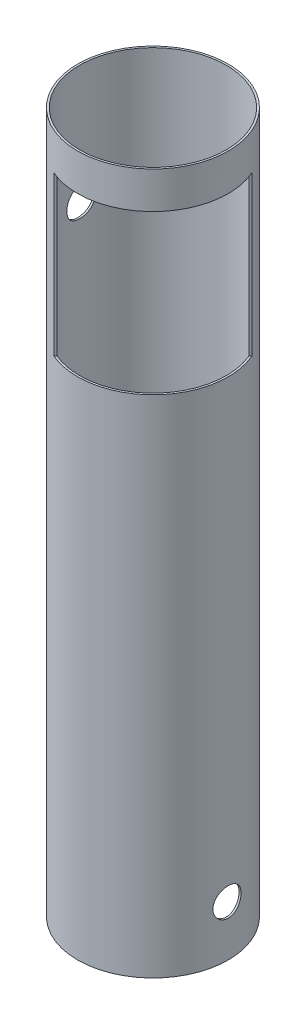
SolidWorks part; units mm, degrees
material "PVC Rígido"
ref_plane "Alzado" through (0, 0, 0) normal (0, 0, 1) x (1, 0, 0)
ref_plane "Planta" through (0, 0, 0) normal (0, 1, 0) x (1, 0, 0)
ref_plane "Vista lateral" through (0, 0, 0) normal (1, 0, 0) x (0, 0, -1)
sketch "Croquis1" plane through (0, 0, 0) normal (0, 1, 0) x (1, 0, 0)
  circle A0 centre (0, 0) radius 55.5
  circle A1 centre (0, 0) radius 57
  dimension "D1" = 111
  dimension "D2" = 114
extrude "Saliente-Extruir1" add sketch "Croquis1" along normal blind 530
ref_plane "Plano1" through (-57, 0, 0) normal (-1, 0, 0) x (0, 0, 1)
sketch "Croquis2" plane through (-57, 0, 0) normal (-1, 0, 0) x (0, 0, 1)
  line L0 (-57, 0) -> (57, 0) construction
  circle A0 centre (0, 440) radius 10.65
  dimension "D1" = 21.3
  dimension "D2" = 440
extrude "Cortar-Extruir1" cut sketch "Croquis2" against normal blind 10
ref_plane "Plano2" through (57, 0, 0) normal (1, 0, 0) x (0, 0, -1)
sketch "Croquis3" plane through (57, 0, 0) normal (1, 0, 0) x (0, 0, -1)
  line L0 (-57, 0) -> (57, 0) construction
  circle A0 centre (0, 38.1) radius 10.65
  dimension "D1" = 21.3
  dimension "D2" = 38.1
extrude "Cortar-Extruir3" cut sketch "Croquis3" against normal blind 10
ref_plane "Plano3" through (40.3051, 0, 40.3051) normal (0.7071, 0, 0.7071) x (0, -1, 0)
sketch "Croquis4" plane through (40.3051, 0, 40.3051) normal (0.7071, 0, 0.7071) x (0, -1, 0)
  line L1 (-502.0992, 60) -> (-382.0992, 60)
  line L2 (-502.0992, 60) -> (-502.0992, -60)
  line L3 (-502.0992, -60) -> (-382.0992, -60)
  line L4 (-382.0992, 60) -> (-382.0992, -60)
  line L6 (0, 57) -> (-530, 57) construction
  dimension "D1" = 120
  dimension "D2" = 120
  dimension "D3" = 3
extrude "Cortar-Extruir4" cut sketch "Croquis4" against normal blind 36
sketch "Croquis6" plane through (-57, 0, 0) normal (-1, 0, 0) x (0, 0, 1)
  line L0 (4.147, 136.2146) -> (-0.0639, 136.2146)
  ellipse E0 centre (2.0415, 134.6611) end of major axis (2.0415, 132.0271) minor radius 2.624 (-0.5585, 135.0165) -> (4.6415, 135.0165) ccw
  ellipse E1 centre (2.0415, 134.6665) end of major axis (-0.5825, 134.6665) minor radius 2.594 (-0.0639, 136.2146) -> (-0.5585, 135.0165) ccw
  ellipse E2 centre (2.0415, 134.6665) end of major axis (-0.5825, 134.6665) minor radius 2.594 (4.6415, 135.0165) -> (4.147, 136.2146) ccw
extrude "Cortar-Extruir5" cut sketch "Croquis6" against normal blind 36
